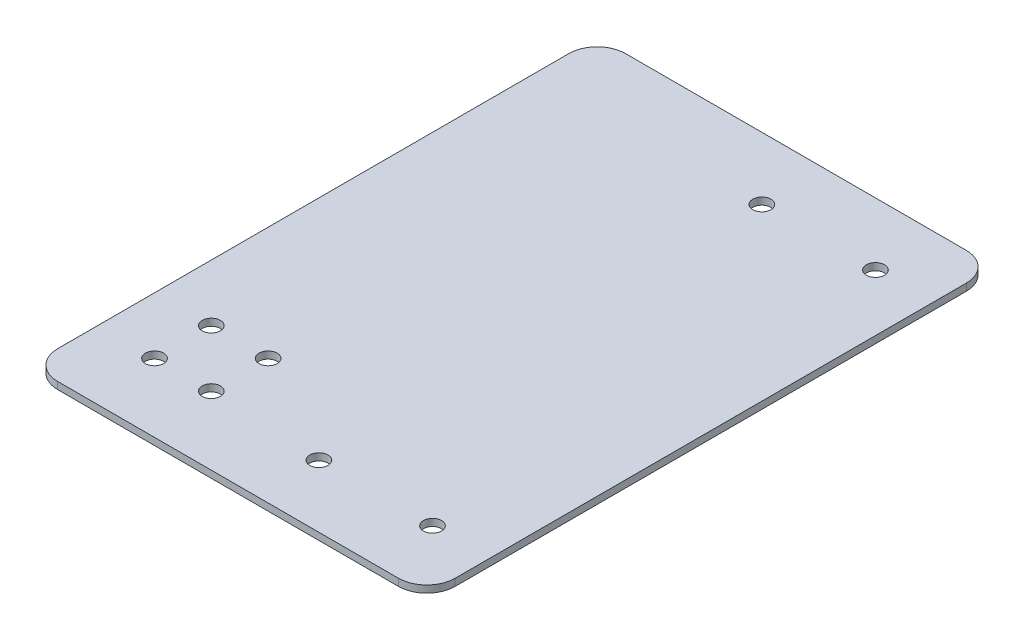
SolidWorks part; units mm, degrees
ref_plane "Front Plane" through (0, 0, 0) normal (0, 0, 1) x (1, 0, 0)
ref_plane "Top Plane" through (0, 0, 0) normal (0, 1, 0) x (1, 0, 0)
ref_plane "Right Plane" through (0, 0, 0) normal (1, 0, 0) x (0, 0, -1)
sketch "Sketch1" plane through (0, 0, 0) normal (0, 1, 0) x (1, 0, 0)
  line L0 (120.65, -35.4965) -> (57.15, -35.4965) construction
  line L1 (-120.65, 63.5) -> (120.65, 63.5)
  line L2 (-120.65, 63.5) -> (-120.65, -63.5)
  line L3 (-120.65, -63.5) -> (120.65, -63.5)
  line L4 (120.65, 63.5) -> (120.65, -63.5)
  line L5 (-120.65, 63.5) -> (120.65, -63.5) construction
  line L6 (-120.65, -63.5) -> (120.65, 63.5) construction
  line L7 (120.65, -49.53) -> (107.95, -49.53) construction
  line L8 (107.95, -49.53) -> (82.55, -49.53) construction
  line L9 (120.65, 49.53) -> (107.95, 49.53) construction
  line L10 (107.95, 49.53) -> (82.55, 49.53) construction
  line L11 (57.15, -35.4965) -> (44.45, -35.4965) construction
  line L12 (44.45, -35.4965) -> (44.45, -48.1965) construction
  line L13 (44.45, -48.1965) -> (57.15, -48.1965) construction
  line L14 (57.15, -48.1965) -> (57.15, -35.4965) construction
  circle A0 centre (82.55, 49.53) radius 2.032
  circle A1 centre (82.55, -49.53) radius 2.032
  circle A2 centre (107.95, -49.53) radius 2.032
  circle A3 centre (107.95, 49.53) radius 2.032
  circle A4 centre (57.15, -35.4965) radius 2.032
  circle A5 centre (44.45, -35.4965) radius 2.032
  circle A6 centre (44.45, -48.1965) radius 2.032
  circle A7 centre (57.15, -48.1965) radius 2.032
  point P0 (0, 0)
  dimension "D7" = 4.064
  dimension "D1" = 241.3
  dimension "D2" = 127
  dimension "D3" = 12.7
  dimension "D4" = 25.4
  dimension "D5" = 13.97
  dimension "D6" = 13.97
  dimension "D8" = 63.5
  dimension "D9" = 12.7
  dimension "D10" = 28.0035
  dimension "D11" = 12.7
extrude "Boss-Extrude1" add sketch "Sketch1" along normal blind 1.5875
sketch "Sketch2" plane through (0, 1.5875, 0) normal (0, 1, 0) x (1, 0, 0)
  line L0 (31.75, 63.5) -> (31.75, -63.5)
  line L1 (-120.65, 63.5) -> (120.65, 63.5) construction
  line L2 (-120.65, -63.5) -> (120.65, -63.5) construction
  circle A0 centre (44.45, -48.1965) radius 2.032 construction
  line M11 (120.65, 63.5) -> (-120.65, 63.5)
  line M12 (-120.65, 63.5) -> (-120.65, -63.5)
  line M13 (-120.65, -63.5) -> (120.65, -63.5)
  dimension "D1" = 12.7
extrude "Cut-Extrude1" cut sketch "Sketch2" against normal through all contours L0 M11 M12 M13
fillet "Fillet1" [suppressed] radius 6.35
fillet "Fillet2" radius 6.35 4 edges at (120.65, 0.7937, -63.5) (120.65, 0.7937, 63.5) (31.75, 0.7937, -63.5) (31.75, 0.7937, 63.5)
